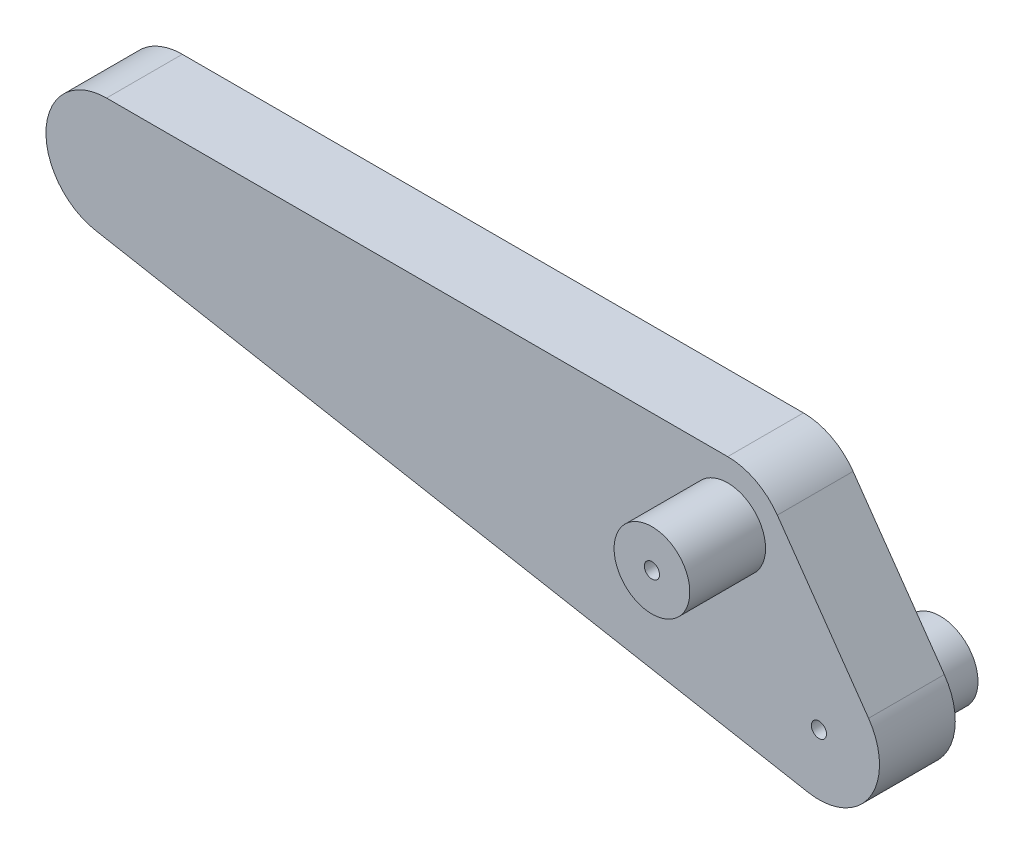
SolidWorks part; units mm, degrees
material "ABS"
ref_plane "Front Plane" through (0, 0, 0) normal (0, 0, 1) x (1, 0, 0)
ref_plane "Top Plane" through (0, 0, 0) normal (0, 1, 0) x (1, 0, 0)
ref_plane "Right Plane" through (0, 0, 0) normal (1, 0, 0) x (0, 0, -1)
sketch "Sketch1" plane through (0, 0, 0) normal (0, 0, 1) x (1, 0, 0)
  line L0 (0, 0) -> (-41, 0)
  line L1 (0, 0) -> (6.0226, -8.6011)
  dimension "D1" = 41
  dimension "D2" = 10.5
  dimension "D3" = 125
sketch "Sketch2" plane through (0, 0, 0) normal (0, 0, 1) x (1, 0, 0)
  line L0 (-41, 4) -> (0, 4)
  line L1 (3.2766, 2.2943) -> (9.2992, -6.3068)
  line L2 (5.3028, -12.5358) -> (-41.7197, -3.9347)
  arc A1 (-41, 4) -> (-41.7197, -3.9347) centre (-41, 0) ccw
  circle A2 centre (0, 0) radius 2.5
  arc A3 (3.2766, 2.2943) -> (0, 4) centre (0, 0) ccw
  circle A4 centre (6.0226, -8.6011) radius 2.5
  arc A5 (5.3028, -12.5358) -> (9.2992, -6.3068) centre (6.0226, -8.6011) ccw
  dimension "D2" = 8
  dimension "D3" = 5
  dimension "D4" = 8
  dimension "D5" = 5
  dimension "D6" = 8
extrude "Boss-Extrude1" add sketch "Sketch2" along normal blind 5
sketch "Sketch3" plane through (0, 0, 5) normal (0, 0, 1) x (1, 0, 0)
  circle A0 centre (6.0226, -8.6011) radius 2.5
  circle A1 centre (6.0226, -8.6011) radius 0.5
  dimension "D1" = 1
  dimension "D2" = 5
extrude "Boss-Extrude2" add sketch "Sketch3" against normal blind 8
sketch "Sketch4" plane through (0, 0, 0) normal (0, 0, -1) x (-1, 0, 0)
  circle A0 centre (0, 0) radius 2.5
  circle A1 centre (0, 0) radius 0.5
  dimension "D1" = 1
  dimension "D2" = 5
extrude "Boss-Extrude3" add sketch "Sketch4" against normal blind 10
